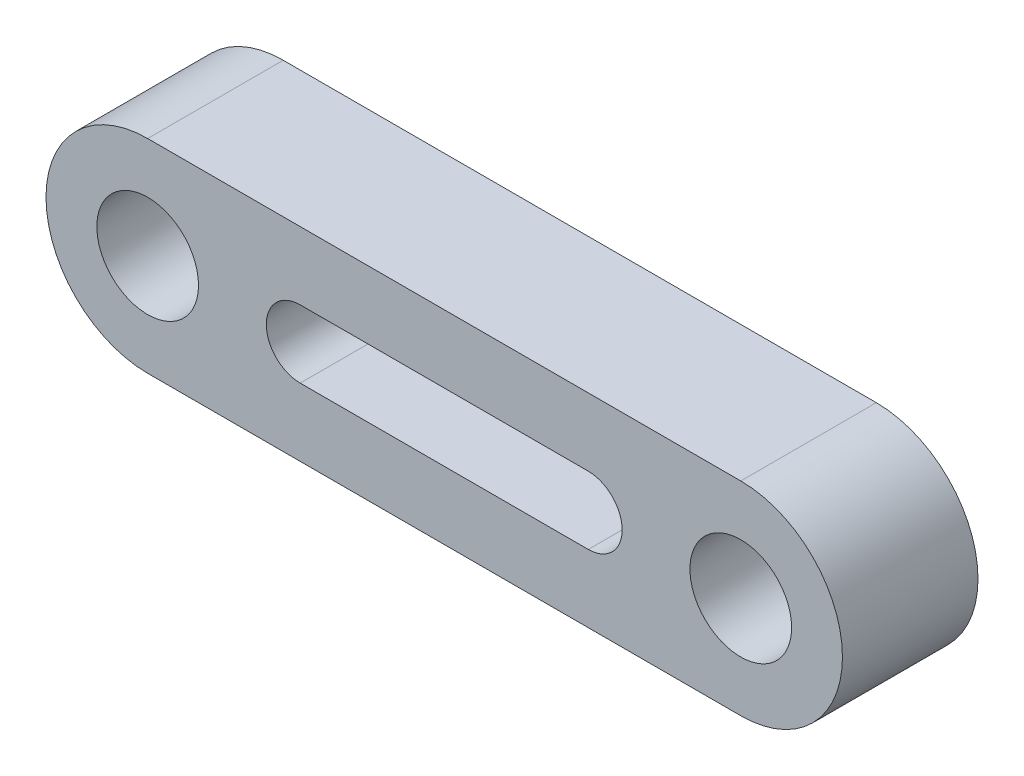
SolidWorks part; units mm, degrees
ref_plane "Plan de face" through (0, 0, 0) normal (0, 0, 1) x (1, 0, 0)
ref_plane "Plan de dessus" through (0, 0, 0) normal (0, 1, 0) x (1, 0, 0)
ref_plane "Plan de droite" through (0, 0, 0) normal (1, 0, 0) x (0, 0, -1)
sketch "Esquisse1" plane through (0, 0, 0) normal (0, 0, 1) x (1, 0, 0)
  line L0 (0, 0) -> (17.5, 0) construction
  line L1 (0, 3) -> (17.5, 3)
  line L2 (0, -3) -> (17.5, -3)
  line L3 (0, 0) -> (0, 1.5) construction
  line L4 (0, 1.5) -> (0, 3) construction
  arc A0 (0, 3) -> (0, -3) centre (0, 0) ccw
  arc A1 (17.5, -3) -> (17.5, 3) centre (17.5, 0) ccw
  circle A2 centre (0, 0) radius 1.5
  circle A3 centre (17.5, 0) radius 1.5
  point P3 (8.75, 0)
  dimension "D1" = 3
  dimension "D2" = 17.5
extrude "Boss.-Extru.1" add sketch "Esquisse1" along normal blind 4
sketch "Esquisse2" plane through (0, 0, 4) normal (0, 0, 1) x (1, 0, 0)
  line L0 (4.5, 0) -> (13, 0) construction
  line L1 (4.5, 1) -> (13, 1)
  line L2 (4.5, -1) -> (13, -1)
  line L3 (0, 0) -> (4.5, 0) construction
  line L4 (13, 0) -> (17.5, 0) construction
  arc A0 (4.5, 1) -> (4.5, -1) centre (4.5, 0) ccw
  arc A1 (13, -1) -> (13, 1) centre (13, 0) ccw
  circle A2 centre (17.5, 0) radius 1.5 construction
  point P3 (8.75, 0)
  dimension "D1" = 2
  dimension "D2" = 4.5
extrude "Enlèv. mat.-Extru.1" cut sketch "Esquisse2" against normal up to next
